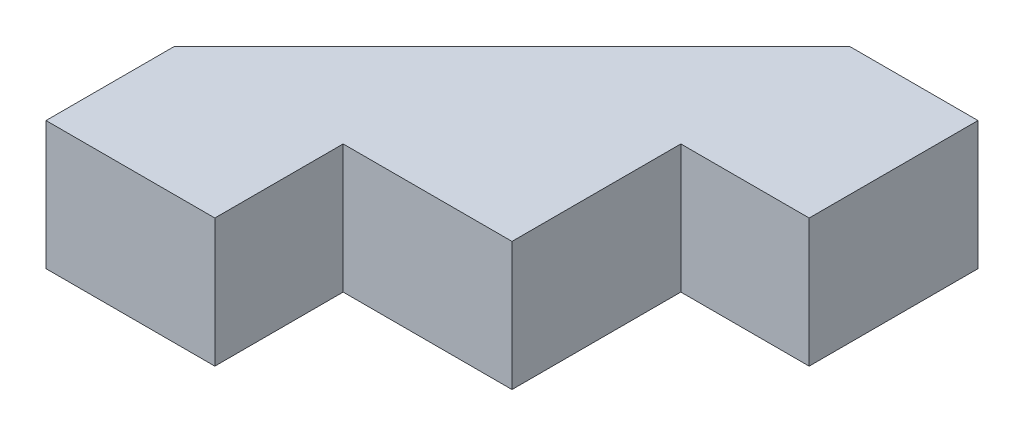
SolidWorks part; units mm, degrees
ref_plane "Front Plane" through (0, 0, 0) normal (0, 0, 1) x (1, 0, 0)
ref_plane "Top Plane" through (0, 0, 0) normal (0, 1, 0) x (1, 0, 0)
ref_plane "Right Plane" through (0, 0, 0) normal (1, 0, 0) x (0, 0, -1)
sketch "Sketch1" plane through (0, 0, 0) normal (0, 1, 0) x (1, 0, 0)
  line L0 (-8.362, -13.6221) -> (4.338, -0.9221)
  line L2 (4.338, -0.9221) -> (9.164, -0.9221)
  line L3 (-8.362, -13.6221) -> (4.338, -13.6221)
  line L4 (4.338, -0.9221) -> (4.338, -13.6221)
  line L5 (4.338, -0.9221) -> (4.338, -7.2721)
  line L6 (4.338, -7.2721) -> (9.164, -7.2721)
  line L7 (9.164, -0.9221) -> (9.164, -7.2721)
  line L8 (-8.362, -13.6221) -> (-2.012, -13.6221)
  line L9 (-8.362, -13.6221) -> (-8.362, -18.4481)
  line L10 (-8.362, -18.4481) -> (-2.012, -18.4481)
  line L11 (-2.012, -13.6221) -> (-2.012, -18.4481)
  dimension "D2" = 12.7
  dimension "D1" = 6.35
  dimension "D3" = 6.35
  dimension "D4" = 4.826
  dimension "D5" = 4.826
  dimension "D6" = 12.7
extrude "Boss-Extrude1" add sketch "Sketch1" along normal blind 4.826 contours L11 L3 L9 L10 | L4 L0 L3 | L7 L2 L4 L6
equation "\"MDF\"= 0.19in"
equation "\"Foamcore\"= .13in"
equation "\"Gmaterial\"= \"MDF\""
equation "\"D4@Sketch1\"=\"MDF\""
equation "\"D5@Sketch1\"=\"MDF\""
equation "\"D1@Boss-Extrude1\"=\"MDF\""
equation "\"PVCID\" = 2.067in"
equation "\"PVCOD\" = 2.375in"
equation "\"GenDiameter\"= 60mm"
equation "\"GenCutDiameter\" = 1.8in"
equation "\"GenCutDistance\" = 1"
equation "\"TowerHeight\" = 6in"
equation "\"TowerFrontBase\" = 3in"
equation "\"FunnelHeight\" = 1in"
equation "\"FunnelAngle\" = 20"
equation "\"TowerSideBase\" = 3in"
equation "\"TowerPanelLength\" = 2in"
equation "\"TowerPanelLeeway\" = 0.5in"
equation "\"BaseLength\" = 9in"
equation "\"BaseWidth\" = 10in"
equation "\"WheelHoleLength\" = 3.25in"
equation "\"WheelHoleWidth\" = 26mm"
equation "\"WheelHoleFromBack\" = 1.5in"
equation "\"DropLength\" = 1in"
equation "\"DropWidth\" = 8.5in"
equation "\"BumperWidth\" = 2in"
equation "\"HoleDiameter\"= 0.25in"
equation "\"SmallHexDiameter\" = 0.185in"
equation "\"SmallHexHeight\" = 0.701in"
equation "\"ScrewSize\" = 0.106in"
equation "\"BigHexDiameter\" = 0.251in"
equation "\"BigHexHeight\" = 0.374in"
equation "\"PCBThickness\" = 0.066in"
equation "\"ConnectorHeight\" = 0.517in"
equation "\"BoardHeight\" = 0.583in"
equation "\"UnoStackHeight\" = 1.351in"
equation "\"UnoStackWidth\" = 3.053in"
equation "\"UnoStackLength\" = 3.152in"
equation "\"HBridgeWidth\" = 1.797in"
equation "\"HBridgeLength\" = 2.236in"
equation "\"DSWidth\" = 1.820in"
equation "\"DSLength\" = 1.833in"
equation "\"StepperWidth\" = 1.799in"
equation "\"StepperLength\" = 2.248in"
equation "\"ULNWidth\" = 1.304in"
equation "\"ULNLength\" = 1.545in"
equation "\"VSwitchHeight\" = 0.392in"
equation "\"VSwitchWidth\" = 0.637in"
equation "\"VSwitchLength\" = 1.097in"
equation "\"SkateWheelDiameter\" = 80mm"
equation "\"SkateWheelThickness\" = 24mm"
equation "\"BaseDistance\" = 3in"
